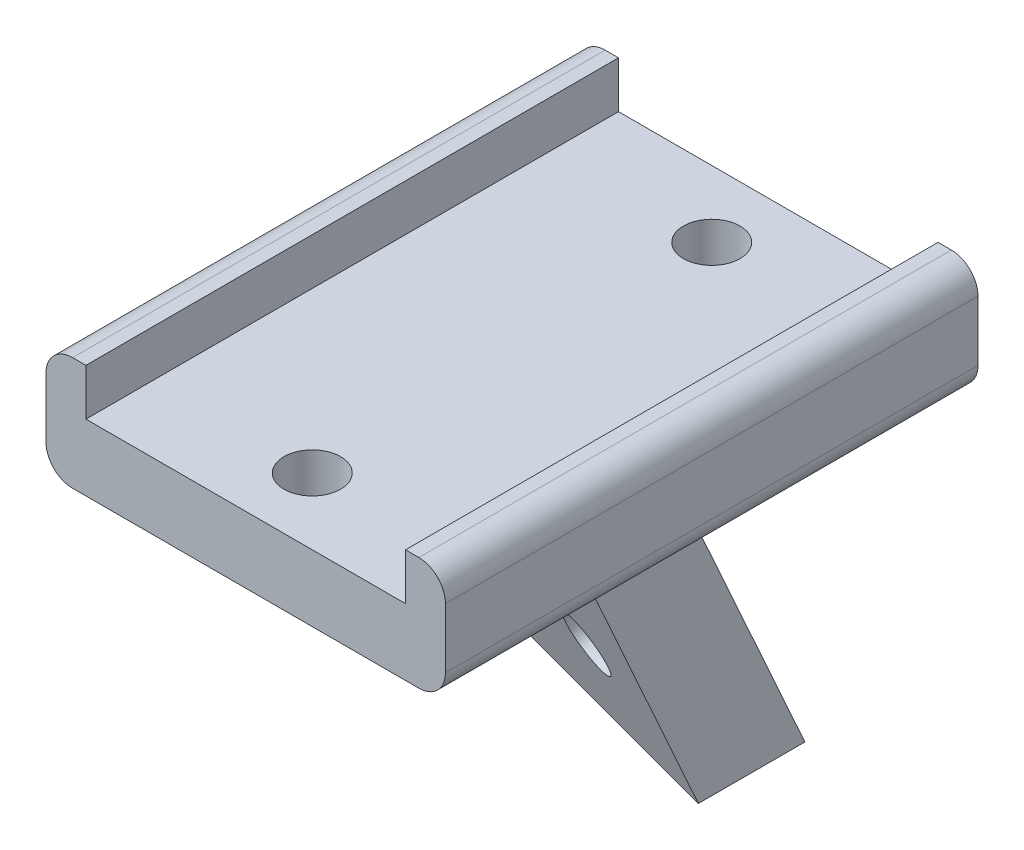
SolidWorks part; units mm, degrees
ref_plane "Front Plane" through (0, 0, 0) normal (0, 0, 1) x (1, 0, 0)
ref_plane "Top Plane" through (0, 0, 0) normal (0, 1, 0) x (1, 0, 0)
ref_plane "Right Plane" through (0, 0, 0) normal (1, 0, 0) x (0, 0, -1)
sketch "Sketch1" plane through (0, 0, 0) normal (0, 1, 0) x (1, 0, 0)
  line L1 (-11, -20) -> (11, -20)
  line L2 (-11, -20) -> (-11, 20)
  line L3 (-11, 20) -> (11, 20)
  line L4 (11, -20) -> (11, 20)
  line L5 (-11, -20) -> (11, 20) construction
  line L6 (-11, 20) -> (11, -20) construction
  circle A0 centre (0, 15) radius 2.125
  circle A1 centre (0, -15) radius 2.125
  point P0 (0, 0)
  dimension "D3" = 30
  dimension "D4" = 15
  dimension "D5" = 4.25
  dimension "D6" = 4.25
  dimension "D1" = 22
  dimension "D2" = 40
extrude "Boss-Extrude1" add sketch "Sketch1" along normal blind 5
sketch "Sketch2" plane through (0, 0, 0) normal (0, -1, 0) x (1, 0, 0)
  line L0 (-11, 0.1051) -> (11, 6)
  line L1 (-11, -20) -> (-11, 20) construction
  line L2 (11, 20) -> (11, -20) construction
  line L3 (11, 6) -> (11, -2)
  line L4 (11, -2) -> (-11, -7.8949)
  line L5 (-11, -7.8949) -> (-11, 0.1051)
  dimension "D1" = 8
  dimension "D2" = 14
  dimension "D3" = 105
sketch "Sketch4" plane through (0, 0, -20) normal (0, 0, -1) x (-1, 0, 0)
  line L0 (-11, 5) -> (-12, 5)
  line L1 (-12, 5) -> (-12, 8.5)
  line L2 (-12, 8.5) -> (-15, 8.5)
  line L3 (-15, 8.5) -> (-15, 0)
  line L4 (-15, 0) -> (-11, 0)
  line L5 (-11, 0) -> (-11, 5)
  line L6 (0, 0) -> (0, 5) construction
  line L7 (-11, 0) -> (11, 0) construction
  line L8 (-11, 5) -> (11, 5) construction
  line L9 (11, 0) -> (11, 5)
  line L10 (15, 0) -> (11, 0)
  line L11 (15, 8.5) -> (15, 0)
  line L12 (12, 8.5) -> (15, 8.5)
  line L13 (12, 5) -> (12, 8.5)
  line L14 (11, 5) -> (12, 5)
  dimension "D1" = 1
  dimension "D2" = 3.5
  dimension "D3" = 3
extrude "Boss-Extrude3" add sketch "Sketch4" against normal up to surface (40 mm away) up to face at (0, 2.5, 20)
fillet "Fillet1" radius 2 4 edges at (15, 0, 0) (-15, 0, 0) (-15, 8.5, 0) (15, 8.5, 0)
ref_plane "Plane1" through (0, -20, 0) normal (0, -1, 0) x (-1, 0, 0)
sketch "Sketch5" plane through (0, -20, 0) normal (0, -1, 0) x (-1, 0, 0)
  line L0 (-11, 3) -> (-11, 11)
  line L1 (-11, 11) -> (11, 16.8949)
  line L2 (11, 16.8949) -> (11, 8.8949)
  line L3 (11, 8.8949) -> (-11, 3)
  line L4 (-13, 20) -> (-13, -20) construction
  line L5 (13, -20) -> (13, 20) construction
  line L6 (13, -20) -> (-13, -20) construction
  dimension "D1" = 8
  dimension "D2" = 2
  dimension "D3" = 2
  dimension "D4" = 105
  dimension "D5" = 23
loft "Loft1" add profiles "Sketch2", "Sketch5"
ref_plane "Plane2" through (1.0403, 1.7471, -3.8825) normal (-0.2374, -0.3986, 0.8859) x (0.9714, -0.0974, 0.2165)
sketch "Sketch6" plane through (1.0403, 1.7471, -3.8825) normal (-0.2374, -0.3986, 0.8859) x (0.9714, -0.0974, 0.2165)
  line L0 (10.2527, -0.8207) -> (10.2527, -22.7524) construction
  line L1 (-12.3945, -3.2398) -> (-12.3945, -25.1715) construction
  line L2 (-12.3945, -3.2398) -> (10.2527, -0.8207) construction
  circle A0 centre (5.2527, -11.4117) radius 2.125
  circle A1 centre (-7.3945, -12.7626) radius 2.125
  point P6 (10.2527, -11.7866)
  dimension "D1" = 4.25
  dimension "D2" = 4.25
  dimension "D3" = 5
  dimension "D4" = 5
  dimension "D5" = 10
  dimension "D6" = 10
extrude "Cut-Extrude1" cut sketch "Sketch6" along normal up to surface (7.0869 mm away) up to face at (5.5, -5, 2.2763)
